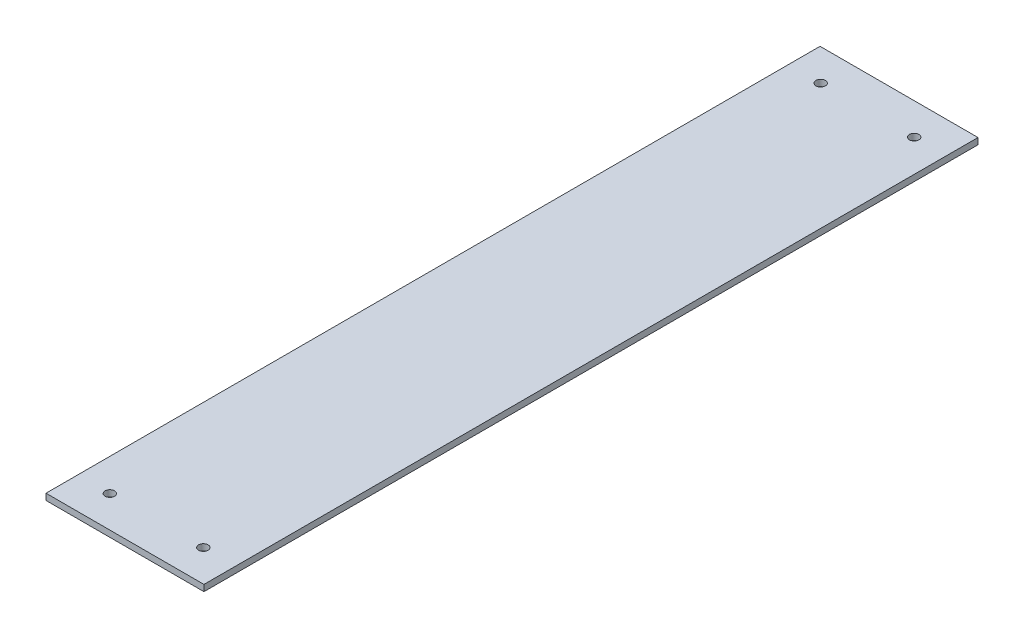
SolidWorks part; units mm, degrees
ref_plane "前视基准面" through (0, 0, 0) normal (0, 0, 1) x (1, 0, 0)
ref_plane "上视基准面" through (0, 0, 0) normal (0, 1, 0) x (1, 0, 0)
ref_plane "右视基准面" through (0, 0, 0) normal (1, 0, 0) x (0, 0, -1)
sketch "草图1" plane through (0, 0, 0) normal (0, 1, 0) x (1, 0, 0)
  line L0 (0, 122.5) -> (50, 122.5) construction
  line L1 (0, 0) -> (50, 0)
  line L2 (0, 0) -> (0, 245)
  line L3 (0, 245) -> (50, 245)
  line L4 (50, 0) -> (50, 245)
  line L5 (25, 0) -> (25, 122.5) construction
  circle A0 centre (10.2, 10) radius 1.5
  circle A1 centre (39.8, 10) radius 1.5
  circle A2 centre (39.8, 235) radius 1.5
  circle A3 centre (10.2, 235) radius 1.5
  dimension "D3" = 3
  dimension "D4" = 29.6
  dimension "D1" = 50
  dimension "D2" = 245
  dimension "D5" = 10
extrude "凸台-拉伸1" add sketch "草图1" along normal blind 2
